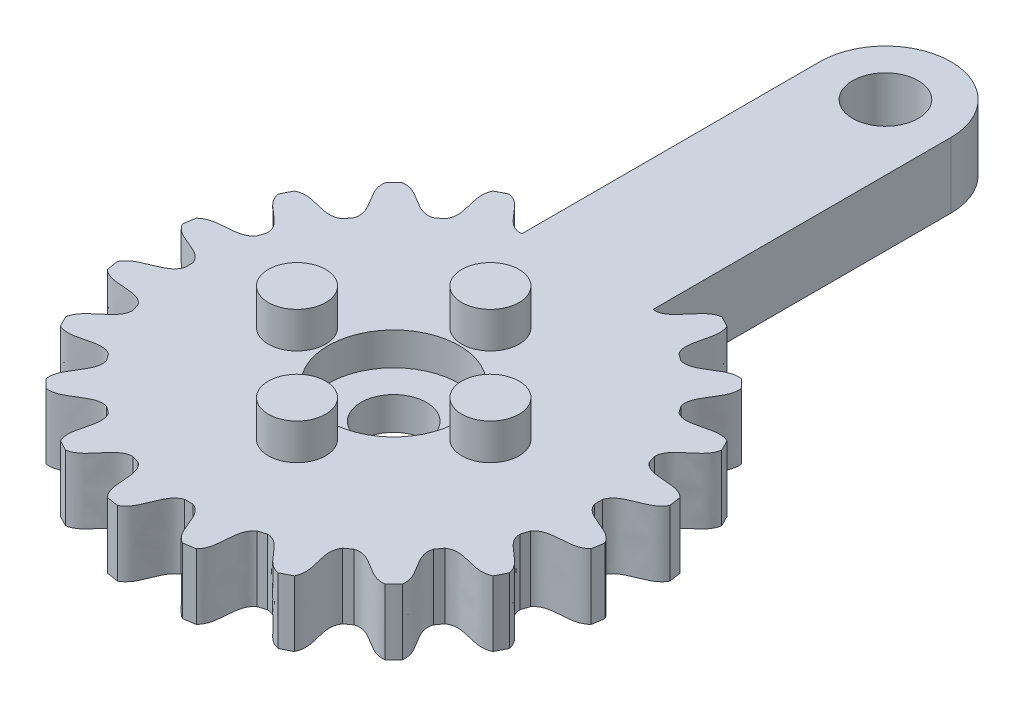
SolidWorks part; units mm, degrees
material "ABS PC"
ref_plane "Plan de face" through (0, 0, 0) normal (0, 0, 1) x (1, 0, 0)
ref_plane "Plan de dessus" through (0, 0, 0) normal (0, 1, 0) x (1, 0, 0)
ref_plane "Plan de droite" through (0, 0, 0) normal (1, 0, 0) x (0, 0, -1)
sketch "Esquisse1" plane through (0, 0, 0) normal (0, 1, 0) x (1, 0, 0)
  line L0 (0, 0) -> (0, 15.3892) construction
  circle A0 centre (0, 0) radius 15
  circle A1 centre (0, 0) radius 2
  dimension "D1" = 30
  dimension "D2" = 4
extrude "Boss.-Extru.1" add sketch "Esquisse1" along normal blind 4
sketch "Esquisse2" plane through (0, 4, 0) normal (0, 1, 0) x (1, 0, 0)
  line L0 (0, 0) -> (0, 16.8006) construction
  line L1 (0.25, 12.5) -> (-0.25, 12.5)
  line L2 (-0.25, 12.5) -> (-1.2103, 12.8292) construction
  line L3 (-1.2103, 12.8292) -> (-1.0465, 14.3774) construction
  line L4 (-1.0465, 14.3774) -> (-1.9814, 14.8686) construction
  line L5 (0.25, 12.5) -> (1.2103, 12.8292) construction
  line L6 (1.2103, 12.8292) -> (1.0465, 14.3774) construction
  line L7 (1.0465, 14.3774) -> (1.9814, 14.8686) construction
  circle A0 centre (0, 0) radius 15 construction
  arc A1 (-1.9814, 14.8686) -> (1.9814, 14.8686) centre (0, 10.3131) cw
  spline S0 degree 3 poles (-0.25, 12.5) (-1.2103, 12.8292) (-1.0465, 14.3774) (-1.9814, 14.8686) knots 0 0 0 0 1 1 1 1
  spline S1 degree 3 poles (0.25, 12.5) (1.2103, 12.8292) (1.0465, 14.3774) (1.9814, 14.8686) knots 0 0 0 0 1 1 1 1
  point P3 (0, 12.5)
  circle M3 centre (0, 0) radius 15
  dimension "D1" = 12.5
  dimension "D2" = 0.5
extrude "Enlèv. mat.-Extru.1" cut sketch "Esquisse2" against normal blind 4 contours L1 S1 S0 M3 | A1 M3
pattern_circular "Répétition circulaire1" count 20 over 360 about axis through (0, 4, 0) along (0, 1, 0) of "Enlèv. mat.-Extru.1"
sketch "Esquisse3" plane through (0, 4, 0) normal (0, 1, 0) x (1, 0, 0)
  line L0 (4, 6.5494) -> (4, 30)
  line L1 (4, 6.5494) -> (-4, 6.5494)
  line L2 (-4, 6.5494) -> (-4, 30)
  line L3 (0, 0) -> (0, 35.2666) construction
  arc A0 (4, 30) -> (-4, 30) centre (0, 30) ccw
  circle A1 centre (0, 30) radius 2
  dimension "D1" = 4
  dimension "D2" = 30
  dimension "D3" = 4
extrude "Boss.-Extru.2" add sketch "Esquisse3" against normal blind 4
sketch "Esquisse4" plane through (0, 4, 0) normal (0, 1, 0) x (1, 0, 0)
  circle A0 centre (0, 0) radius 13.8407 construction
sketch "Esquisse5" plane through (0, 4, 0) normal (0, 1, 0) x (1, 0, 0)
  circle A0 centre (0, 0) radius 5.9 construction
  circle A1 centre (5.9, 0) radius 1.75
  circle A2 centre (0, -5.9) radius 1.75
  circle A3 centre (-5.9, 0) radius 1.75
  circle A4 centre (0, 5.9) radius 1.75
  point P14 (0, 0)
  dimension "D1" = 3.5
  dimension "D2" = 11.8
  dimension "D3" = 4
extrude "Boss.-Extru.3" add sketch "Esquisse5" along normal blind 2.2
sketch "Esquisse6" plane through (0, 4, 0) normal (0, 1, 0) x (1, 0, 0)
  circle A0 centre (0, 0) radius 4
  dimension "D1" = 8
extrude "Enlèv. mat.-Extru.2" cut sketch "Esquisse6" against normal blind 2
equation "\"2.2.00mm\"=10"
